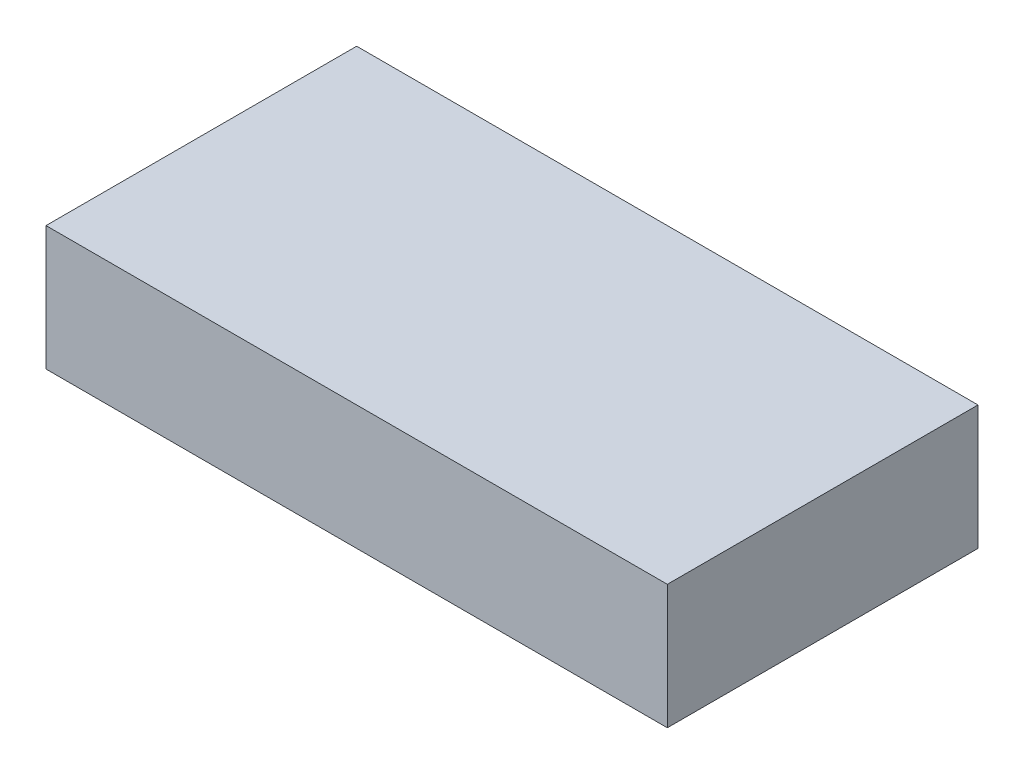
SolidWorks part; units mm, degrees
ref_plane "Front Plane" through (0, 0, 0) normal (0, 0, 1) x (1, 0, 0)
ref_plane "Top Plane" through (0, 0, 0) normal (0, 1, 0) x (1, 0, 0)
ref_plane "Right Plane" through (0, 0, 0) normal (1, 0, 0) x (0, 0, -1)
sketch "Sketch1" plane through (0, 0, 0) normal (0, 1, 0) x (1, 0, 0)
  line L1 (0, 0) -> (16, 0)
  line L2 (0, 0) -> (0, 8)
  line L3 (0, 8) -> (16, 8)
  line L4 (16, 0) -> (16, 8)
  dimension "D1" = 16
  dimension "D2" = 8
extrude "Boss-Extrude1" add sketch "Sketch1" along normal blind 3.2
shell "Shell1" thickness 1.6
